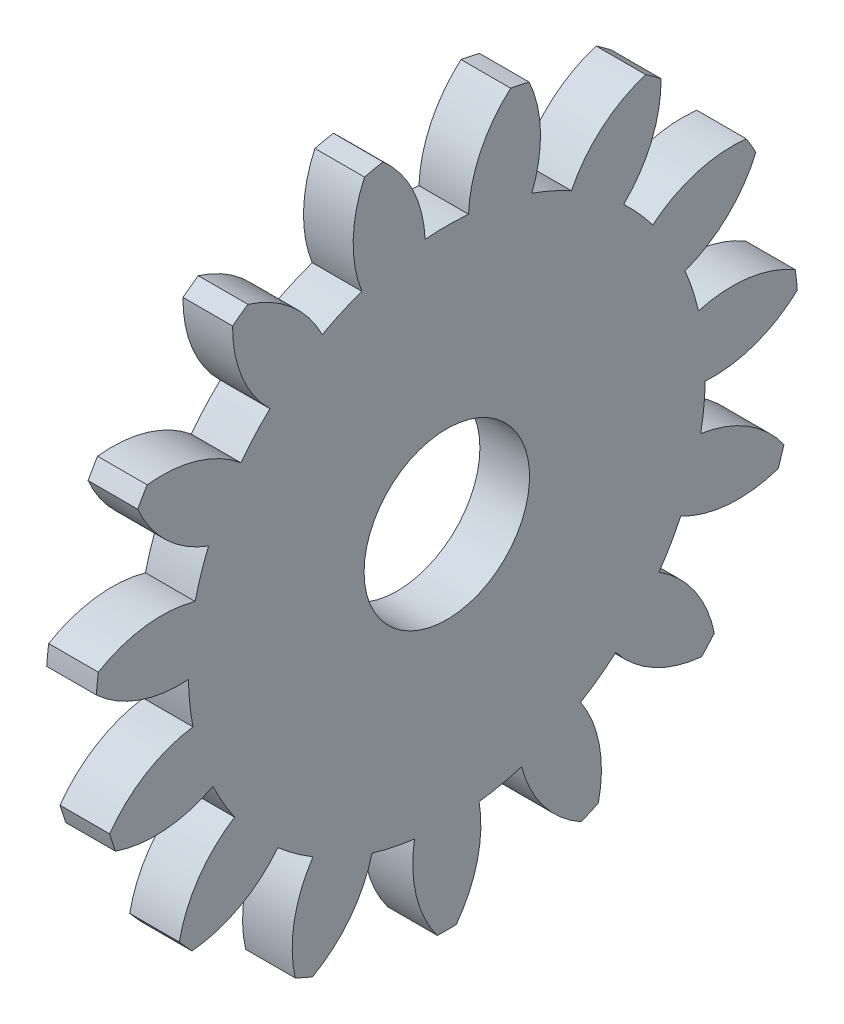
SolidWorks part; units mm, degrees
ref_plane "Plane1" through (0, 0, 0) normal (0, 0, 1) x (1, 0, 0)
ref_plane "Plane2" through (0, 0, 0) normal (0, 1, 0) x (1, 0, 0)
ref_plane "Plane3" through (0, 0, 0) normal (1, 0, 0) x (0, 0, -1)
sketch "HoldingSke" plane through (0, 0, 0) normal (0, 1, 0) x (1, 0, 0)
  line L0 (0, 0) -> (0.1932, -0.0518)
  line L1 (-15, 0) -> (100, 0) construction
  line L2 (0, 0) -> (-2.1039, 2.3779)
  line L3 (0, 0) -> (-11.863, 4.5341)
  line L4 (0, 0) -> (8.3417, 2.2352)
  line L5 (0, 0) -> (-46.8476, -17.4728)
  line L6 (0, 0) -> (-4.9738, -3.3558)
  line L7 (-2.1039, 2.3779) -> (8.6586, 51.2059)
  line L8 (-76.2, 54.61) -> (-73.4, 54.61)
  line L9 (-71.009, 38.7566) -> (-53.1078, 45.2721)
  line L10 (-76.2, 71.12) -> (104.1128, 71.12)
  line L11 (0, 0) -> (-6, 0)
  line L12 (-76.2, 101.6) -> (-76.033, 101.6)
  line L13 (24.9733, 27.94) -> (52.9518, 28.4284)
  line L14 (24.9733, 27.94) -> (24.9743, 27.94)
  line L15 (24.9733, 27.94) -> (100.4006, 29.5858)
  line L16 (-63.627, -5) -> (-12.827, -5)
  circle A0 centre (0, 0) radius 10
  circle A1 centre (0, 0) radius 31.249
  circle A2 centre (0, 0) radius 37.5
  circle A3 centre (0, 0) radius 10
  dimension "Ap" = 20
  dimension "H" = 19.05
  dimension "Pitch_radius" = 180.3128
  dimension "Addendum_fac" = 1
  dimension "Dedendum_fac" = 1.25
  dimension "Clearance_fac" = 0.25
  dimension "Dedendum_add" = 0.001
  dimension "Module" = 5
sketch "BasProSke" plane through (0, 0, 0) normal (0, 1, 0) x (1, 0, 0)
  line L0 (-10, 0) -> (60, 0) construction
  line L1 (0, 0) -> (0, 42.5)
  line L2 (0, 0) -> (6, 0)
  line L3 (6, 0) -> (6, 42.5)
  line L4 (6, 42.5) -> (0, 42.5)
revolve "Base-Revolve" add sketch "BasProSke" angle 360 about L0
sketch "TooCutSke" plane through (0, 0, 0) normal (1, 0, 0) x (0, 0, -1)
  line L1 (0, 0) -> (0, 107) construction
  line L2 (0, 0) -> (-4.2118, 37.2627) construction
  line L3 (0, 0) -> (-15.5202, 73.017) construction
  line L4 (-4.2118, 37.2627) -> (-7.7601, 36.5085) construction
  arc A0 (2.6245, 31.1386) -> (-2.6245, 31.1386) centre (0, 0) ccw
  arc A1 (7.7397, 41.8152) -> (-7.7397, 41.8152) centre (0, 0) ccw
  circle A2 centre (0, 0) radius 37.5 construction
  circle A3 centre (0, 0) radius 35.2385 construction
  arc A4 (-2.6245, 31.1386) -> (-7.7397, 41.8152) centre (-17.6118, 30.5217) ccw
  arc A5 (7.7397, 41.8152) -> (2.6245, 31.1386) centre (17.6118, 30.5217) ccw
extrude "ToothCut" cut sketch "TooCutSke" along normal through all
fillet "Breaks" [suppressed] radius 0.1
fillet "RootFillets" [suppressed] radius 1.251
pattern_circular "TeethCuts" count 15 every 24 about axis through (-10, 0, 0) along (1, 0, 0) of "ToothCut", "RootFillets", "Breaks"
sketch "HubNeaOneSke" plane through (0, 0, 0) normal (-1, 0, 0) x (0, 0, 1)
  circle A0 centre (0, 0) radius 31.249
extrude "HubNearOne" [suppressed] add sketch "HubNeaOneSke" along normal blind 44.0001
sketch "HubNeaBotSke" plane through (0, 0, 0) normal (-1, 0, 0) x (0, 0, 1)
  circle A0 centre (0, 0) radius 31.249
extrude "HubNearBoth" [suppressed] add sketch "HubNeaBotSke" along normal blind 22
ref_plane "FarPln" through (6, 0, 0) normal (1, 0, 0) x (0, 0, -1)
sketch "HubFarSke" plane through (6, 0, 0) normal (1, 0, 0) x (0, 0, -1)
  circle A0 centre (0, 0) radius 31.249
extrude "HubFar" [suppressed] add sketch "HubFarSke" along normal blind 22
sketch "BorSke" plane through (0, 0, 0) normal (1, 0, 0) x (0, 0, -1)
  circle A0 centre (0, 0) radius 10
extrude "Bore" cut sketch "BorSke" along normal mid plane 100.0001
sketch "KeySke" plane through (0, 0, 0) normal (1, 0, 0) x (0, 0, -1)
  line L0 (-3, 0) -> (-3, 12.8)
  line L1 (-3, 12.8) -> (3, 12.8)
  line L2 (3, 12.8) -> (3, 0)
  line L3 (0, 0) -> (0, 34) construction
  line L4 (-3, 0) -> (3, 0)
extrude "Keyway" [suppressed] cut sketch "KeySke" along normal mid plane 100.0001
pattern_circular "Keyway2" [suppressed] count 2 every 90 about axis through (-10, 0, 0) along (1, 0, 0)
equation "' \"Module@HoldingSke\" = 6.35"
equation "' \"Num_teeth@HoldingSke\" = 12"
equation "' \"Ap@HoldingSke\" =  20"
equation "' \"Ap@HoldingSke\" = 20"
equation "' \"Width@HoldingSke\" = 0.5 * 25.4"
equation "' \"Hub_dia@HoldingSke\"= 1 * 25.4"
equation "' \"Hub_dia@HoldingSke\" = 1 * 25.4"
equation "' \"Overall_len@HoldingSke\" = 1.0 * 25.4"
equation "' \"Bore@HoldingSke\" = 0.75 * 25.4"
equation "' \"T_dim@HoldingSke\" = 0.1 * 25.4"
equation "' \"Width@KeySke\" = 0.25 * 25.4"
equation "' \"Show_teeth@HoldingSke\" = 13"
equation "' \"Backlash@HoldingSke\" = 0.009 * 25.4"
equation "' \"Addendum_fac@HoldingSke\" = 1.0"
equation "' \"Dedendum_fac@HoldingSke\" = 1.25"
equation "' \"Dedendum_add@HoldingSke\" = 0.00005 * 25.4"
equation "' \"Clearance_fac@HoldingSke\" = 0.25"
equation "\"Pitch@HoldingSke\" = 1 / \"Module@HoldingSke\""
equation "\"Overcut_dia@TooCutSke\" = (\"Num_teeth@HoldingSke\" + 2 * \"Addendum_fac@HoldingSke\") / \"Pitch@HoldingSke\" + 0.002 * 25.4"
equation "\"Pitch_dia@TooCutSke\" = \"Num_teeth@HoldingSke\" / \"Pitch@HoldingSke\""
equation "\"Base_dia@TooCutSke\" = \"Num_teeth@HoldingSke\" / \"Pitch@HoldingSke\" * cos((\"Ap@HoldingSke\"  * 3.14159265 / 180))"
equation "\"Root_dia@TooCutSke\" = (\"Num_teeth@HoldingSke\" + 2) / \"Pitch@HoldingSke\" - 2 * (\"Addendum_fac@HoldingSke\" + \"Dedendum_fac@HoldingSke\") / \"Pitch@HoldingSke\" - \"Dedendum_add@HoldingSke\" * 2"
equation "\"Half_ang@TooCutSke\" = 180 / \"Num_teeth@HoldingSke\""
equation "\"Half_CT@TooCutSke\" = \"Num_teeth@HoldingSke\" / \"Pitch@HoldingSke\" * sin((3.14159265 / 2 / \"Num_teeth@HoldingSke\")) / 2 - 7 * \"Backlash@HoldingSke\" / 4"
equation "\"Flank_rad@TooCutSke\" = \"Num_teeth@HoldingSke\" / \"Pitch@HoldingSke\" / 5"
equation "\"Radius@RootFillets\" = \"Clearance_fac@HoldingSke\" / \"Pitch@HoldingSke\" + \"Dedendum_add@HoldingSke\""
equation "\"Break_rad@Breaks\" = 0.02 / \"Pitch@HoldingSke\""
equation "\"Thickness@HoldingSke\" = \"Width@HoldingSke\""
equation "\"OAL@HoldingSke\" = \"Thickness@HoldingSke\""
equation "\"MHD@HoldingSke\" = (\"Num_teeth@HoldingSke\" + 2) / \"Pitch@HoldingSke\" - 2 * (\"Addendum_fac@HoldingSke\" + \"Dedendum_fac@HoldingSke\")  / \"Pitch@HoldingSke\" - \"Dedendum_add@HoldingSke\" * 2"
equation "\"MBD@HoldingSke\" = (\"Num_teeth@HoldingSke\" + 2) / \"Pitch@HoldingSke\" - 2 * (\"Addendum_fac@HoldingSke\" + \"Dedendum_fac@HoldingSke\")  / \"Pitch@HoldingSke\" - \"Dedendum_add@HoldingSke\" * 2 - 0.002 * 25.4"
equation "\"MHD@HoldingSke\" = ((sgn( \"MHD@HoldingSke\" - \"Hub_dia@HoldingSke\" )-1)*( \"MHD@HoldingSke\" - \"Hub_dia@HoldingSke\" ))/-2+ \"Hub_dia@HoldingSke\""
equation "\"MBD@HoldingSke\" = ((sgn( \"MBD@HoldingSke\" - \"Bore@HoldingSke\" )-1)*( \"MBD@HoldingSke\" - \"Bore@HoldingSke\" ))/-2+ \"Bore@HoldingSke\""
equation "\"OAL@HoldingSke\" = ((sgn( \"OAL@HoldingSke\" - \"Overall_len@HoldingSke\" )+1)*( \"OAL@HoldingSke\" - \"Overall_len@HoldingSke\" ))/2 + \"Overall_len@HoldingSke\" + 0.000002 * 25.4"
equation "\"Num_teeth@TeethCuts\" = int( \"Show_teeth@HoldingSke\" ) + 1"
equation "\"Num_teeth@TeethCuts\" = ((sgn( \"Num_teeth@TeethCuts\" - \"Num_teeth@HoldingSke\" )-1)*( \"Num_teeth@TeethCuts\" - \"Num_teeth@HoldingSke\" ))/-2+ \"Num_teeth@HoldingSke\""
equation "\"Num_teeth@TeethCuts\" = ((sgn( \"Num_teeth@TeethCuts\" - 2.0)+1)*( \"Num_teeth@TeethCuts\" - 2.0))/2 +2.0"
equation "\"Angle@TeethCuts\" = 360.0 / \"Num_teeth@HoldingSke\""
equation "\"Diameter@BasProSke\" = (\"Num_teeth@HoldingSke\" + 2 * \"Addendum_fac@HoldingSke\") / \"Pitch@HoldingSke\""
equation "\"Thickness@BasProSke\"  = \"Thickness@HoldingSke\""
equation "' \"Fillet_rad@BasProSke\" =  \"Thickness@HoldingSke\" * 0.05"
equation "' \"Fillet_rad@BasProSke\" = \"Thickness@HoldingSke\" * 0.05"
equation "\"MHD@HoldingSke\" = ((sgn( \"MHD@HoldingSke\" - \"Root_dia@TooCutSke\" )-1)*( \"MHD@HoldingSke\" - \"Root_dia@TooCutSke\" ))/-2+ \"Root_dia@TooCutSke\""
equation "\"Diameter@HubNeaOneSke\" = \"MHD@HoldingSke\""
equation "\"Length@HubNearOne\" = \"OAL@HoldingSke\" - \"Thickness@BasProSke\""
equation "\"Diameter@HubNeaBotSke\" = \"MHD@HoldingSke\""
equation "\"Length@HubNearBoth\" = ( \"OAL@HoldingSke\" - \"Thickness@BasProSke\" ) / 2.0"
equation "\"Thickness@FarPln\" = \"Thickness@BasProSke\""
equation "\"Diameter@HubFarSke\" = \"MHD@HoldingSke\""
equation "\"Length@HubFar\" = ( \"OAL@HoldingSke\" - \"Thickness@BasProSke\" ) / 2.0"
equation "\"Diameter@BorSke\" = \"MBD@HoldingSke\""
equation "\"D1@Bore\" = \"OAL@HoldingSke\" * 2.0"
equation "\"D1@Keyway\" = \"OAL@HoldingSke\" * 2.0"
equation "\"Offset@KeySke\" = \"T_dim@HoldingSke\" + \"MBD@HoldingSke\" / 2.0"
